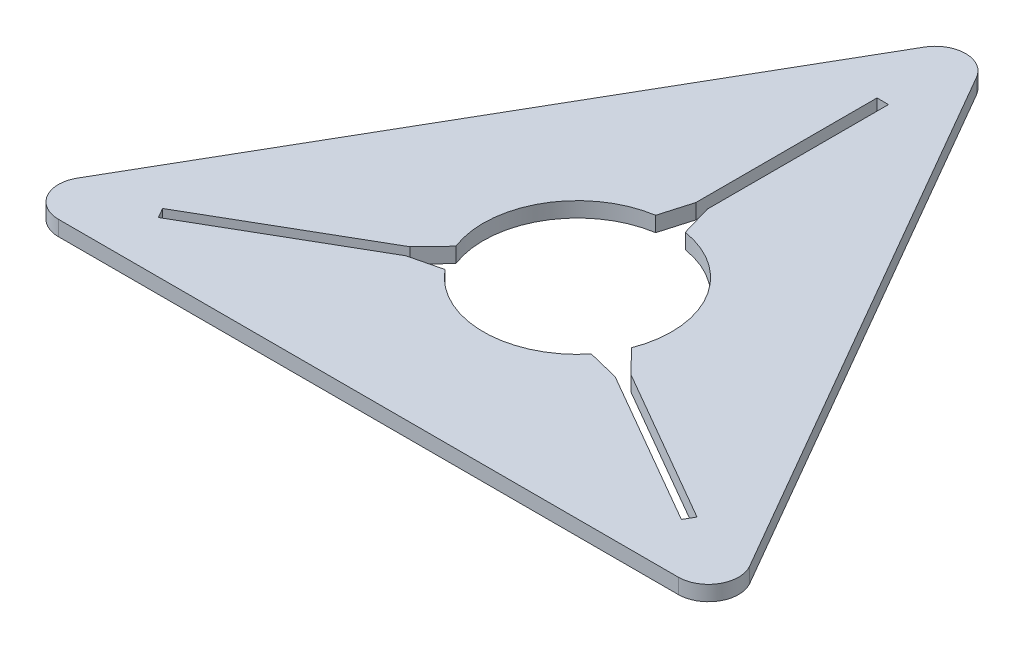
SolidWorks part; units mm, degrees
ref_plane "Front Plane" through (0, 0, 0) normal (0, 0, 1) x (1, 0, 0)
ref_plane "Top Plane" through (0, 0, 0) normal (0, 1, 0) x (1, 0, 0)
ref_plane "Right Plane" through (0, 0, 0) normal (1, 0, 0) x (0, 0, -1)
sketch "Sketch1" plane through (0, 0, 0) normal (0, 1, 0) x (1, 0, 0)
  line L0 (-77.5526, -12.3987) -> (74.8474, 251.5659)
  line L1 (74.8474, 251.5659) -> (227.2474, -12.3987)
  line L2 (227.2474, -12.3987) -> (-77.5526, -12.3987)
  line L3 (-77.5526, -12.3987) -> (39.3349, 55.0863) construction
  line L4 (74.8474, 251.5659) -> (74.8474, 118.8239) construction
  line L5 (227.2474, -12.3987) -> (111.6478, 54.3428) construction
  line L6 (72.4344, 115.1399) -> (72.4344, 204.0399)
  line L7 (72.4344, 204.0399) -> (77.2604, 204.0399)
  line L8 (77.2604, 204.0399) -> (77.2604, 115.1399)
  line L9 (110.3056, 57.904) -> (187.2953, 13.454)
  line L10 (187.2953, 13.454) -> (184.8823, 9.2745)
  line L11 (184.8823, 9.2745) -> (107.8926, 53.7245)
  line L12 (41.8022, 53.7245) -> (-35.1875, 9.2745)
  line L13 (-35.1875, 9.2745) -> (-37.6005, 13.454)
  line L14 (-37.6005, 13.454) -> (39.3892, 57.904)
  line L15 (72.4344, 127.8399) -> (68.6244, 114.7218)
  line L16 (77.2604, 127.8399) -> (81.0704, 114.7218)
  line L17 (121.3041, 51.554) -> (111.8484, 61.4126)
  line L18 (118.8911, 47.3745) -> (105.6254, 50.6341)
  line L19 (30.8037, 47.3745) -> (44.0693, 50.6341)
  line L20 (28.3907, 51.554) -> (37.8463, 61.4126)
  circle A0 centre (74.8474, 75.5895) radius 39.624
  point P2 (74.8474, 75.5895)
  point P23 (74.8474, 75.5895)
  point P36 (74.8474, 75.5895)
  dimension "D7" = 79.248
  dimension "D1" = 60
  dimension "D2" = 60
  dimension "D3" = 0
  dimension "D4" = 30
  dimension "D5" = 30
  dimension "D6" = 30
  dimension "D8" = 304.8
  dimension "D9" = 2.413
  dimension "D10" = 4.826
  dimension "D11" = 88.9
  dimension "D13" = 12.7
  dimension "D14" = 12.7
  dimension "D15" = 3.81
  dimension "D16" = 3.81
  dimension "D12" = 3
  dimension "D17" = 3
extrude "Boss-Extrude1" add sketch "Sketch1" along normal blind 6.35 contours L2 L1 L0 A0 L9 L10 L11 L12 L13 L14 L6 L7 L8
fillet "Fillet1" radius 12.7 3 edges at (74.8474, 3.175, -251.5659) (227.2474, 3.175, 12.3987) (-77.5526, 3.175, 12.3987)
